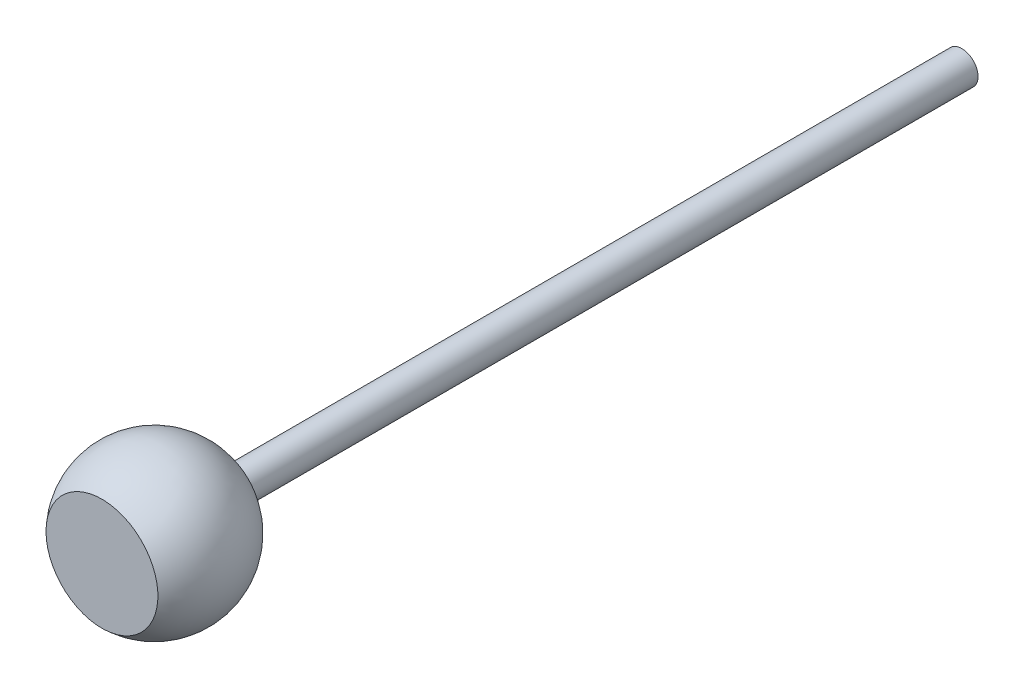
SolidWorks part; units mm, degrees
ref_plane "Front Plane" through (0, 0, 0) normal (0, 0, 1) x (1, 0, 0)
ref_plane "Top Plane" through (0, 0, 0) normal (0, 1, 0) x (1, 0, 0)
ref_plane "Right Plane" through (0, 0, 0) normal (1, 0, 0) x (0, 0, -1)
sketch "Sketch1" plane through (0, 0, 0) normal (0, 0, 1) x (1, 0, 0)
  circle A0 centre (0, 0) radius 2
extrude "Boss-Extrude1" add sketch "Sketch1" along normal blind 40
sketch "Sketch2" plane through (0, 0, 0) normal (0, 1, 0) x (1, 0, 0)
  line L0 (-2, -40) -> (2, -40) construction
  line L1 (-9.5, -40) -> (9.5, -40)
  arc A0 (9.5, -40) -> (-9.5, -40) centre (0, -40) ccw
revolve "Revolve1" add sketch "Sketch2" angle 360 about L1
sketch "Sketch5" plane through (0, 0, 0) normal (0, 0, -1) x (-1, 0, 0)
  circle A0 centre (0, 0) radius 2
extrude "Boss-Extrude2" add sketch "Sketch5" along normal blind 60
sketch "Sketch6" plane through (0, 0, 0) normal (1, 0, 0) x (0, 0, -1)
  line L1 (-46.5, 0) -> (-46.5, 12.0128)
  line L2 (-46.5, 12.0128) -> (-54.3298, 12.0128)
  line L3 (-54.3298, -12.092) -> (-54.3298, 12.0128)
  line L4 (-54.3298, -12.092) -> (-46.5, -12.092)
  line L5 (-46.5, -12.092) -> (-46.5, 0)
extrude "Cut-Extrude1" cut sketch "Sketch6" against normal through all both and the other way through all
